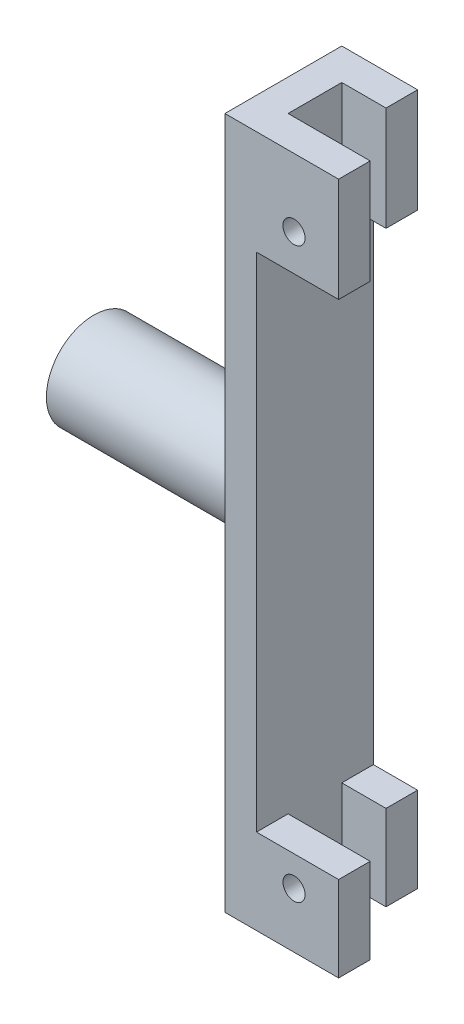
SolidWorks part; units mm, degrees
ref_plane "정면" through (0, 0, 0) normal (0, 0, 1) x (1, 0, 0)
ref_plane "윗면" through (0, 0, 0) normal (0, 1, 0) x (1, 0, 0)
ref_plane "우측면" through (0, 0, 0) normal (1, 0, 0) x (0, 0, -1)
sketch "스케치1" plane through (0, 0, 0) normal (0, 0, 1) x (1, 0, 0)
  line L1 (18, -109.5) -> (-18, -109.5)
  line L2 (18, -109.5) -> (18, 109.5)
  line L3 (18, 109.5) -> (-18, 109.5)
  line L4 (-18, -109.5) -> (-18, 109.5)
  line L5 (18, -109.5) -> (-18, 109.5) construction
  line L6 (18, 109.5) -> (-18, -109.5) construction
  point P0 (0, 0)
  dimension "D1" = 219
  dimension "D2" = 36
extrude "보스-돌출1" add sketch "스케치1" along normal blind 37
sketch "스케치2" plane through (0, 0, 0) normal (0, 0, 1) x (1, 0, 0)
  line L0 (18, -109.5) -> (18, 109.5) construction
  line L1 (-8, 76.5) -> (72.768, 76.5)
  line L2 (-8, 76.5) -> (-8, -82.5)
  line L3 (-8, -82.5) -> (72.768, -82.5)
  line L4 (72.768, 76.5) -> (72.768, -82.5)
  line L5 (18, 109.5) -> (-18, 109.5) construction
  dimension "D1" = 26
  dimension "D2" = 159
  dimension "D3" = 33
extrude "컷-돌출1" cut sketch "스케치2" along normal through all
sketch "스케치9" plane through (0, 0, 0) normal (0, 0, 1) x (1, 0, 0)
  line L0 (18, 76.5) -> (18, 109.5) construction
  line L1 (-8, 109.5) -> (18, 109.5)
  line L2 (-8, 109.5) -> (-8, -109.5)
  line L3 (-8, -109.5) -> (18, -109.5)
  line L4 (18, 109.5) -> (18, -109.5)
  line L5 (18, 109.5) -> (-18, 109.5) construction
  dimension "D1" = 26
  dimension "D2" = 219
extrude "컷-돌출7" cut sketch "스케치9" along normal blind 17 from offset 10
sketch "스케치10" plane through (0, 0, 0) normal (0, 0, 1) x (1, 0, 0)
  line L0 (18, 76.5) -> (18, 109.5) construction
  line L1 (18, 126.5) -> (6, 126.5)
  line L2 (18, 126.5) -> (18, -109.5)
  line L3 (18, -109.5) -> (6, -109.5)
  line L4 (6, 126.5) -> (6, -109.5)
  line L5 (-18, -109.5) -> (18, -109.5) construction
  dimension "D1" = 236
  dimension "D2" = 12
extrude "컷-돌출8" cut sketch "스케치10" along normal blind 17
sketch "스케치11" plane through (0, 0, 0) normal (0, 0, 1) x (1, 0, 0)
  line L1 (-18, 109.5) -> (-18, -109.5) construction
  line L4 (18, 76.5) -> (-8, 76.5) construction
  line L5 (-8, -82.5) -> (18, -82.5) construction
  circle A0 centre (3.8782, 88) radius 3.5
  circle A1 centre (3.8782, -92) radius 3.5
  dimension "D1" = 7
  dimension "D2" = 8
  dimension "D3" = 18.3782
  dimension "D5" = 9.5
extrude "컷-돌출11" cut sketch "스케치11" against normal blind 17 from surface at 37 starting at face at (2.5, -1.5, 37)
ref_plane "평면1" through (-18, 0, 0) normal (-1, 0, 0) x (0, 0, 1)
sketch "스케치25" plane through (-18, 0, 0) normal (-1, 0, 0) x (0, 0, 1)
  circle A0 centre (18.5, 0) radius 15
extrude "보스-돌출3" add sketch "스케치25" along normal blind 60
sketch "스케치26" plane through (0, 0, 0) normal (1, 0, 0) x (0, 0, -1)
  line L0 (-18.5, 120.2838) -> (-18.5, -134.3248) construction
  line L1 (0, 0) -> (-86.5204, 0) construction
  circle A0 centre (-18.5, 0) radius 11
  dimension "D1" = 22
extrude "컷-돌출13" cut sketch "스케치26" along normal blind 3 from surface at -78 starting at face at (-78, 0, 33.5)
